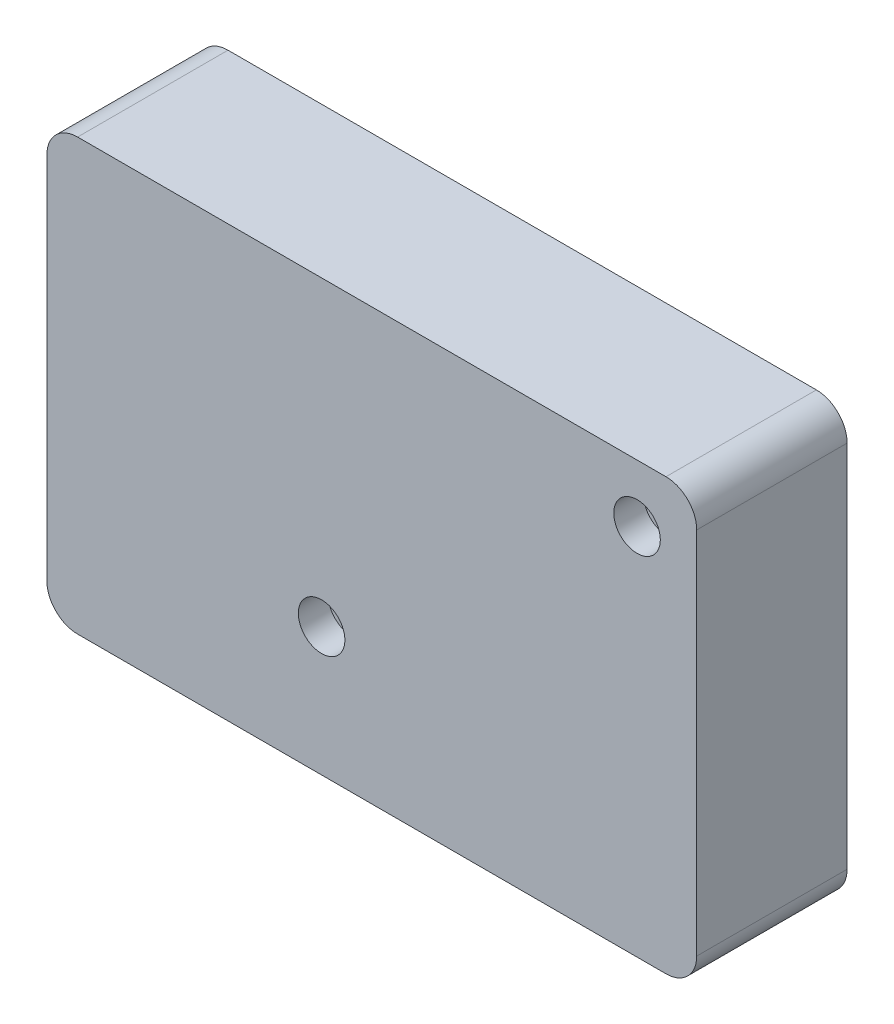
SolidWorks part; units mm, degrees
ref_plane "前视基准面" through (0, 0, 0) normal (0, 0, 1) x (1, 0, 0)
ref_plane "上视基准面" through (0, 0, 0) normal (0, 1, 0) x (1, 0, 0)
ref_plane "右视基准面" through (0, 0, 0) normal (1, 0, 0) x (0, 0, -1)
sketch "草图1" plane through (0, 0, 0) normal (0, 0, 1) x (1, 0, 0)
  line L0 (33.2419, -17.3338) -> (33.2419, -5.4548)
  line L4 (33.2419, -5.4548) -> (33.2419, 25.6013)
  line L5 (-36.2952, -18.4088) -> (32.1669, -18.4088)
  line L6 (-36.2952, 26.6762) -> (32.1669, 26.6762)
  line L7 (-37.3701, -17.3338) -> (-37.3701, 25.6013)
  line L8 (-37.3701, -11.3206) -> (33.2419, -11.3943)
  line L2616 (29.2206, 25.1602) -> (28.7969, 25.1936)
  line L2617 (28.7969, 25.1936) -> (28.3732, 25.1602)
  line L2618 (28.3732, 25.1602) -> (27.96, 25.061)
  line L2619 (27.96, 25.061) -> (27.5673, 24.8984)
  line L2620 (27.5673, 24.8984) -> (27.2049, 24.6763)
  line L2621 (27.2049, 24.6763) -> (26.8818, 24.4003)
  line L2622 (26.8818, 24.4003) -> (26.6058, 24.0772)
  line L2623 (26.6058, 24.0772) -> (26.3837, 23.7148)
  line L2624 (26.3837, 23.7148) -> (26.2211, 23.3222)
  line L2625 (26.2211, 23.3222) -> (26.1219, 22.9089)
  line L2626 (26.1219, 22.9089) -> (26.0885, 22.4852)
  line L2627 (26.0885, 22.4852) -> (26.1219, 22.0616)
  line L2628 (26.1219, 22.0616) -> (26.2211, 21.6483)
  line L2629 (26.2211, 21.6483) -> (26.3837, 21.2557)
  line L2630 (26.3837, 21.2557) -> (26.6058, 20.8933)
  line L2631 (26.6058, 20.8933) -> (26.8818, 20.5701)
  line L2632 (26.8818, 20.5701) -> (27.2049, 20.2941)
  line L2633 (27.2049, 20.2941) -> (27.5673, 20.0721)
  line L2634 (27.5673, 20.0721) -> (27.96, 19.9094)
  line L2635 (27.96, 19.9094) -> (28.3732, 19.8102)
  line L2636 (28.3732, 19.8102) -> (28.7969, 19.7769)
  line L2637 (28.7969, 19.7769) -> (29.2206, 19.8102)
  line L2638 (29.2206, 19.8102) -> (29.6338, 19.9094)
  line L2639 (29.6338, 19.9094) -> (30.0264, 20.0721)
  line L2640 (30.0264, 20.0721) -> (30.3888, 20.2941)
  line L2641 (30.3888, 20.2941) -> (30.712, 20.5701)
  line L2642 (30.712, 20.5701) -> (30.988, 20.8933)
  line L2643 (30.988, 20.8933) -> (31.21, 21.2557)
  line L2644 (31.21, 21.2557) -> (31.3727, 21.6483)
  line L2645 (31.3727, 21.6483) -> (31.4719, 22.0616)
  line L2646 (31.4719, 22.0616) -> (31.5052, 22.4852)
  line L2647 (31.5052, 22.4852) -> (31.4719, 22.9089)
  line L2648 (31.4719, 22.9089) -> (31.3727, 23.3222)
  line L2649 (31.3727, 23.3222) -> (31.21, 23.7148)
  line L2650 (31.21, 23.7148) -> (30.988, 24.0772)
  line L2651 (30.988, 24.0772) -> (30.712, 24.4003)
  line L2652 (30.712, 24.4003) -> (30.3888, 24.6763)
  line L2653 (30.3888, 24.6763) -> (30.0264, 24.8984)
  line L2654 (30.0264, 24.8984) -> (29.6338, 25.061)
  line L2655 (29.6338, 25.061) -> (29.2206, 25.1602)
  line L2808 (-6.6331, -8.3493) -> (-6.3142, -8.1539)
  line L2809 (-6.3142, -8.1539) -> (-5.991, -7.8779)
  line L2810 (-5.991, -7.8779) -> (-5.715, -7.5547)
  line L2811 (-5.715, -7.5547) -> (-5.493, -7.1923)
  line L2812 (-5.493, -7.1923) -> (-5.3303, -6.7997)
  line L2813 (-5.3303, -6.7997) -> (-5.2311, -6.3864)
  line L2814 (-5.2311, -6.3864) -> (-5.1978, -5.9628)
  line L2815 (-5.1978, -5.9628) -> (-5.2311, -5.5391)
  line L2816 (-5.2311, -5.5391) -> (-5.3303, -5.1258)
  line L2817 (-5.3303, -5.1258) -> (-5.493, -4.7332)
  line L2818 (-5.493, -4.7332) -> (-5.715, -4.3708)
  line L2819 (-5.715, -4.3708) -> (-5.991, -4.0477)
  line L2820 (-5.991, -4.0477) -> (-6.3142, -3.7717)
  line L2821 (-6.3142, -3.7717) -> (-6.6766, -3.5496)
  line L2822 (-6.6766, -3.5496) -> (-7.0692, -3.387)
  line L2823 (-7.0692, -3.387) -> (-7.4824, -3.2878)
  line L2824 (-7.4824, -3.2878) -> (-7.9061, -3.2544)
  line L2825 (-7.9061, -3.2544) -> (-8.3298, -3.2878)
  line L2826 (-8.3298, -3.2878) -> (-8.743, -3.387)
  line L2827 (-8.743, -3.387) -> (-9.1357, -3.5496)
  line L2828 (-9.1357, -3.5496) -> (-9.4981, -3.7717)
  line L2829 (-9.4981, -3.7717) -> (-9.8212, -4.0477)
  line L2830 (-9.8212, -4.0477) -> (-10.0972, -4.3708)
  line L2831 (-10.0972, -4.3708) -> (-10.3193, -4.7332)
  line L2832 (-10.3193, -4.7332) -> (-10.4819, -5.1258)
  line L2833 (-10.4819, -5.1258) -> (-10.5811, -5.5391)
  line L2834 (-10.5811, -5.5391) -> (-10.6145, -5.9628)
  line L2835 (-10.6145, -5.9628) -> (-10.5811, -6.3864)
  line L2836 (-10.5811, -6.3864) -> (-10.4819, -6.7997)
  line L2837 (-10.4819, -6.7997) -> (-10.3193, -7.1923)
  line L2838 (-10.3193, -7.1923) -> (-10.0972, -7.5547)
  line L2839 (-10.0972, -7.5547) -> (-9.8212, -7.8779)
  line L2840 (-9.8212, -7.8779) -> (-9.4981, -8.1539)
  line L2841 (-9.4981, -8.1539) -> (-9.1792, -8.3493)
  line L3455 (29.2206, 25.1602) -> (28.7969, 25.1936)
  line L3456 (28.7969, 25.1936) -> (28.3732, 25.1602)
  line L3457 (28.3732, 25.1602) -> (27.96, 25.061)
  line L3458 (27.96, 25.061) -> (27.5673, 24.8984)
  line L3459 (27.5673, 24.8984) -> (27.2049, 24.6763)
  line L3460 (27.2049, 24.6763) -> (26.8818, 24.4003)
  line L3461 (26.8818, 24.4003) -> (26.6058, 24.0772)
  line L3462 (26.6058, 24.0772) -> (26.3837, 23.7148)
  line L3463 (26.3837, 23.7148) -> (26.2211, 23.3222)
  line L3464 (26.2211, 23.3222) -> (26.1219, 22.9089)
  line L3465 (26.1219, 22.9089) -> (26.0885, 22.4852)
  line L3466 (26.0885, 22.4852) -> (26.1219, 22.0616)
  line L3467 (26.1219, 22.0616) -> (26.2211, 21.6483)
  line L3468 (26.2211, 21.6483) -> (26.3837, 21.2557)
  line L3469 (26.3837, 21.2557) -> (26.6058, 20.8933)
  line L3470 (26.6058, 20.8933) -> (26.8818, 20.5701)
  line L3471 (26.8818, 20.5701) -> (27.2049, 20.2941)
  line L3472 (27.2049, 20.2941) -> (27.5673, 20.0721)
  line L3473 (27.5673, 20.0721) -> (27.96, 19.9094)
  line L3474 (27.96, 19.9094) -> (28.3732, 19.8102)
  line L3475 (28.3732, 19.8102) -> (28.7969, 19.7769)
  line L3476 (28.7969, 19.7769) -> (29.2206, 19.8102)
  line L3477 (29.2206, 19.8102) -> (29.6338, 19.9094)
  line L3478 (29.6338, 19.9094) -> (30.0264, 20.0721)
  line L3479 (30.0264, 20.0721) -> (30.3888, 20.2941)
  line L3480 (30.3888, 20.2941) -> (30.712, 20.5701)
  line L3481 (30.712, 20.5701) -> (30.988, 20.8933)
  line L3482 (30.988, 20.8933) -> (31.21, 21.2557)
  line L3483 (31.21, 21.2557) -> (31.3727, 21.6483)
  line L3484 (31.3727, 21.6483) -> (31.4719, 22.0616)
  line L3485 (31.4719, 22.0616) -> (31.5052, 22.4852)
  line L3486 (31.5052, 22.4852) -> (31.4719, 22.9089)
  line L3487 (31.4719, 22.9089) -> (31.3727, 23.3222)
  line L3488 (31.3727, 23.3222) -> (31.21, 23.7148)
  line L3489 (31.21, 23.7148) -> (30.988, 24.0772)
  line L3490 (30.988, 24.0772) -> (30.712, 24.4003)
  line L3491 (30.712, 24.4003) -> (30.3888, 24.6763)
  line L3492 (30.3888, 24.6763) -> (30.0264, 24.8984)
  line L3493 (30.0264, 24.8984) -> (29.6338, 25.061)
  line L3494 (29.6338, 25.061) -> (29.2206, 25.1602)
  line L4236 (-7.4824, -3.2878) -> (-7.9061, -3.2544)
  line L4237 (-7.9061, -3.2544) -> (-8.3298, -3.2878)
  line L4238 (-8.3298, -3.2878) -> (-8.743, -3.387)
  line L4239 (-8.743, -3.387) -> (-9.1357, -3.5496)
  line L4240 (-9.1357, -3.5496) -> (-9.4981, -3.7717)
  line L4241 (-9.4981, -3.7717) -> (-9.8212, -4.0477)
  line L4242 (-9.8212, -4.0477) -> (-10.0972, -4.3708)
  line L4243 (-10.0972, -4.3708) -> (-10.3193, -4.7332)
  line L4244 (-10.3193, -4.7332) -> (-10.4819, -5.1258)
  line L4245 (-10.4819, -5.1258) -> (-10.5811, -5.5391)
  line L4246 (-10.5811, -5.5391) -> (-10.6145, -5.9628)
  line L4247 (-10.6145, -5.9628) -> (-10.5811, -6.3864)
  line L4248 (-10.5811, -6.3864) -> (-10.4819, -6.7997)
  line L4249 (-10.4819, -6.7997) -> (-10.3193, -7.1923)
  line L4250 (-10.3193, -7.1923) -> (-10.0972, -7.5547)
  line L4251 (-10.0972, -7.5547) -> (-9.8212, -7.8779)
  line L4252 (-9.8212, -7.8779) -> (-9.4981, -8.1539)
  line L4253 (-9.4981, -8.1539) -> (-9.1357, -8.3759)
  line L4254 (-9.1357, -8.3759) -> (-8.743, -8.5386)
  line L4255 (-8.743, -8.5386) -> (-8.3298, -8.6378)
  line L4256 (-8.3298, -8.6378) -> (-7.9061, -8.6711)
  line L4257 (-7.9061, -8.6711) -> (-7.4824, -8.6378)
  line L4258 (-7.4824, -8.6378) -> (-7.0692, -8.5386)
  line L4259 (-7.0692, -8.5386) -> (-6.6766, -8.3759)
  line L4260 (-6.6766, -8.3759) -> (-6.3142, -8.1539)
  line L4261 (-6.3142, -8.1539) -> (-5.991, -7.8779)
  line L4262 (-5.991, -7.8779) -> (-5.715, -7.5547)
  line L4263 (-5.715, -7.5547) -> (-5.493, -7.1923)
  line L4264 (-5.493, -7.1923) -> (-5.3303, -6.7997)
  line L4265 (-5.3303, -6.7997) -> (-5.2311, -6.3864)
  line L4266 (-5.2311, -6.3864) -> (-5.1978, -5.9628)
  line L4267 (-5.1978, -5.9628) -> (-5.2311, -5.5391)
  line L4268 (-5.2311, -5.5391) -> (-5.3303, -5.1258)
  line L4269 (-5.3303, -5.1258) -> (-5.493, -4.7332)
  line L4270 (-5.493, -4.7332) -> (-5.715, -4.3708)
  line L4271 (-5.715, -4.3708) -> (-5.991, -4.0477)
  line L4272 (-5.991, -4.0477) -> (-6.3142, -3.7717)
  line L4273 (-6.3142, -3.7717) -> (-6.6766, -3.5496)
  line L4274 (-6.6766, -3.5496) -> (-7.0692, -3.387)
  line L4275 (-7.0692, -3.387) -> (-7.4824, -3.2878)
  line L6751 (-40.2351, 12.9602) -> (-37.3701, 12.9602)
  line L6763 (-40.2351, 4.0702) -> (-37.3701, 4.1337)
  line L6764 (-40.2351, 4.0702) -> (-40.2351, 12.9602)
  circle A1 centre (33.2419, -5.4548) radius 0.04
  circle A3 centre (33.2419, -5.4548) radius 0.04
  circle A7 centre (33.2419, -5.4548) radius 0.04
  circle A8 centre (33.2419, -5.4548) radius 0.04
  arc A1492 (32.1669, -18.4088) -> (33.2419, -17.3338) centre (32.1669, -17.3338) ccw
  arc A1495 (33.2419, 25.6013) -> (32.1669, 26.6762) centre (32.1669, 25.6013) ccw
  arc A1498 (-36.2952, 26.6762) -> (-37.3701, 25.6013) centre (-36.2952, 25.6013) ccw
  arc A1501 (-37.3701, -17.3338) -> (-36.2952, -18.4088) centre (-36.2952, -17.3338) ccw
  circle A1904 centre (28.7969, 22.4852) radius 1.25
  circle A1905 centre (28.7969, 22.4852) radius 1.3008
  circle A1906 centre (28.7969, 22.4852) radius 1.25
  circle A1907 centre (28.7969, 22.4852) radius 1.25
  circle A1908 centre (28.7969, 22.4852) radius 1.3008
  circle A1909 centre (28.7969, 22.4852) radius 0.8
  circle A1910 centre (-7.9061, -5.9628) radius 1.25
  circle A1911 centre (-7.9061, -5.9628) radius 1.3008
  circle A1912 centre (-7.9061, -5.9628) radius 1.25
  circle A1913 centre (-7.9061, -5.9628) radius 1.25
  circle A1914 centre (-7.9061, -5.9628) radius 1.3008
  circle A1915 centre (-7.9061, -5.9628) radius 0.8
  circle A2317 centre (32.4709, 10.6882) radius 0.0635
  circle A2321 centre (32.4709, 10.6882) radius 0.0635
  circle A3495 centre (-40.2351, 12.9602) radius 0.0381
  circle A3503 centre (-37.3701, 4.1337) radius 0.0381
  circle A3517 centre (-37.3701, 4.1337) radius 0.0381
  circle A3521 centre (-40.2351, 4.0702) radius 0.0381
  circle A3522 centre (-37.3701, 4.1337) radius 0.0381
  circle A3523 centre (-40.2351, 4.0702) radius 0.0381
  circle A3524 centre (-40.2351, 12.9602) radius 0.0381
  circle A3525 centre (-36.7351, 11.6902) radius 0.0381
  circle A3529 centre (-36.7351, 5.3402) radius 0.0381
  dimension "D1" = 70.612
  dimension "D2" = 45.085
sketch "草图4" plane through (0, 0, 0) normal (0, 0, 1) x (1, 0, 0)
  line L1 (32.1649, -18.4088) -> (-36.2951, -18.4088)
  line L2 (33.2399, -17.3338) -> (33.2399, 25.6062)
  line L3 (32.1649, 26.6812) -> (-36.2951, 26.6812)
  line L4 (-37.3701, -17.3338) -> (-37.3701, 25.6062)
  line L5 (33.2399, -18.4088) -> (-37.3701, 26.6812) construction
  line L6 (33.2399, 26.6812) -> (-37.3701, -18.4088) construction
  arc A0 (32.1649, -18.4088) -> (33.2399, -17.3338) centre (32.1649, -17.3338) ccw
  arc A1 (-36.2951, -18.4088) -> (-37.3701, -17.3338) centre (-36.2951, -17.3338) cw
  arc A2 (-37.3701, 25.6062) -> (-36.2951, 26.6812) centre (-36.2951, 25.6062) cw
  arc A3 (33.2399, 25.6062) -> (32.1649, 26.6812) centre (32.1649, 25.6062) ccw
  point P0 (-2.0651, 4.1362)
  dimension "D3" = 1.075
  dimension "D1" = 70.61
  dimension "D2" = 45.09
extrude "凸台-拉伸1" add sketch "草图4" against normal blind 15
shell "抽壳1" thickness 2.5
sketch "草图5" plane through (0, 0, 0) normal (0, 0, -1) x (-1, 0, 0)
  line L0 (36.2952, 26.6762) -> (-32.1669, 26.6762) construction
  circle A0 centre (-28.7969, 22.4852) radius 4.191
  circle A1 centre (7.9061, -5.9628) radius 4.191
extrude "凸台-拉伸2" add sketch "草图5" along normal blind 2.5
sketch "草图6" plane through (0, 0, 0) normal (0, 0, -1) x (-1, 0, 0)
  circle A0 centre (7.9061, -5.9628) radius 2.7083
  circle A1 centre (-28.7969, 22.4852) radius 2.7083
extrude "切除-拉伸1" cut sketch "草图6" against normal up to next and the other way blind 1
sketch "草图7" plane through (0, 0, 0) normal (0, 0, -1) x (-1, 0, 0)
  circle A0 centre (7.9061, -5.9628) radius 1.65
  circle A1 centre (-28.7969, 22.4852) radius 1.65
extrude "切除-拉伸2" cut sketch "草图7" against normal through all both and the other way through all
sketch "草图8" plane through (-39.8701, 0, 0) normal (-1, 0, 0) x (0, 0, 1)
  line L1 (-3.7, 3.2764) -> (-3.7, 14.3847)
  line L3 (-3.7, 3.2764) -> (-15, 3.2764)
  line L4 (-15, 25.6062) -> (-15, -17.3338) construction
  line L5 (-15, 3.2764) -> (-15, 14.3847)
  line L6 (-15, 14.3847) -> (-3.7, 14.3847)
extrude "切除-拉伸3" cut sketch "草图8" against normal blind 3
